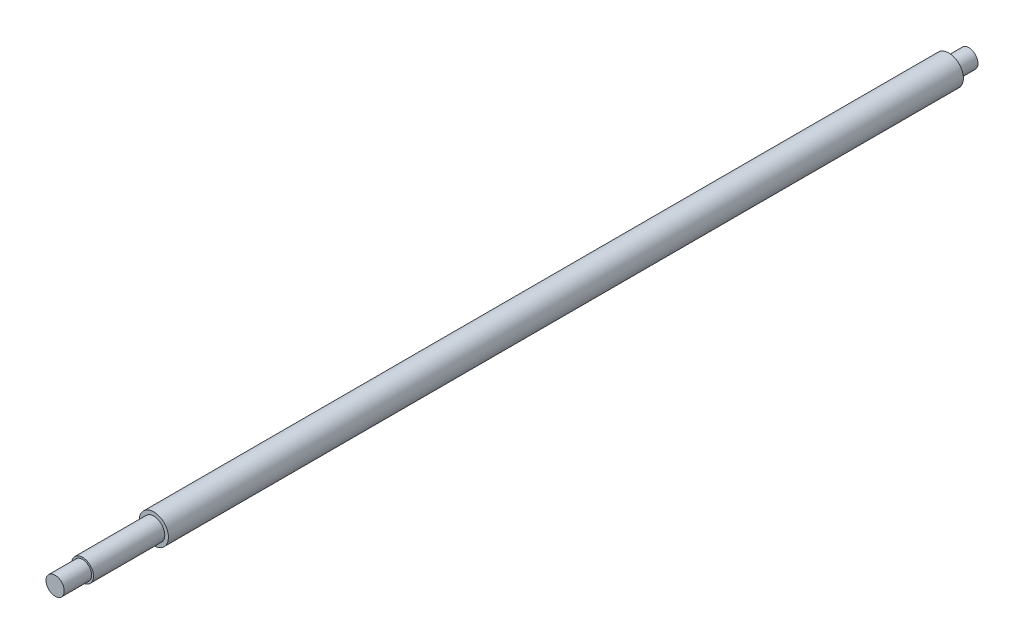
SolidWorks part; units mm, degrees
ref_plane "Front Plane" through (0, 0, 0) normal (0, 0, 1) x (1, 0, 0)
ref_plane "Top Plane" through (0, 0, 0) normal (0, 1, 0) x (1, 0, 0)
ref_plane "Right Plane" through (0, 0, 0) normal (1, 0, 0) x (0, 0, -1)
sketch "Sketch1" plane through (0, 0, 0) normal (0, 1, 0) x (1, 0, 0)
  line L0 (0, 0) -> (5, 0)
  line L1 (5, 0) -> (5, 15)
  line L2 (5, 15) -> (6, 15)
  line L3 (6, 15) -> (6, 54)
  line L4 (6, 54) -> (8, 54)
  line L5 (8, 54) -> (8, 489)
  line L6 (8, 489) -> (5, 489)
  line L7 (5, 489) -> (5, 500)
  line L8 (5, 500) -> (0, 500)
  line L9 (0, 500) -> (0, 0)
  line L10 (0, 0) -> (0, 749.2783) construction
  dimension "D1" = 500
  dimension "D2" = 15
  dimension "D3" = 39
  dimension "D4" = 10
  dimension "D5" = 12
  dimension "D6" = 10
  dimension "D7" = 11
  dimension "D8" = 16
revolve "Revolve1" add sketch "Sketch1" angle 360 about L10
